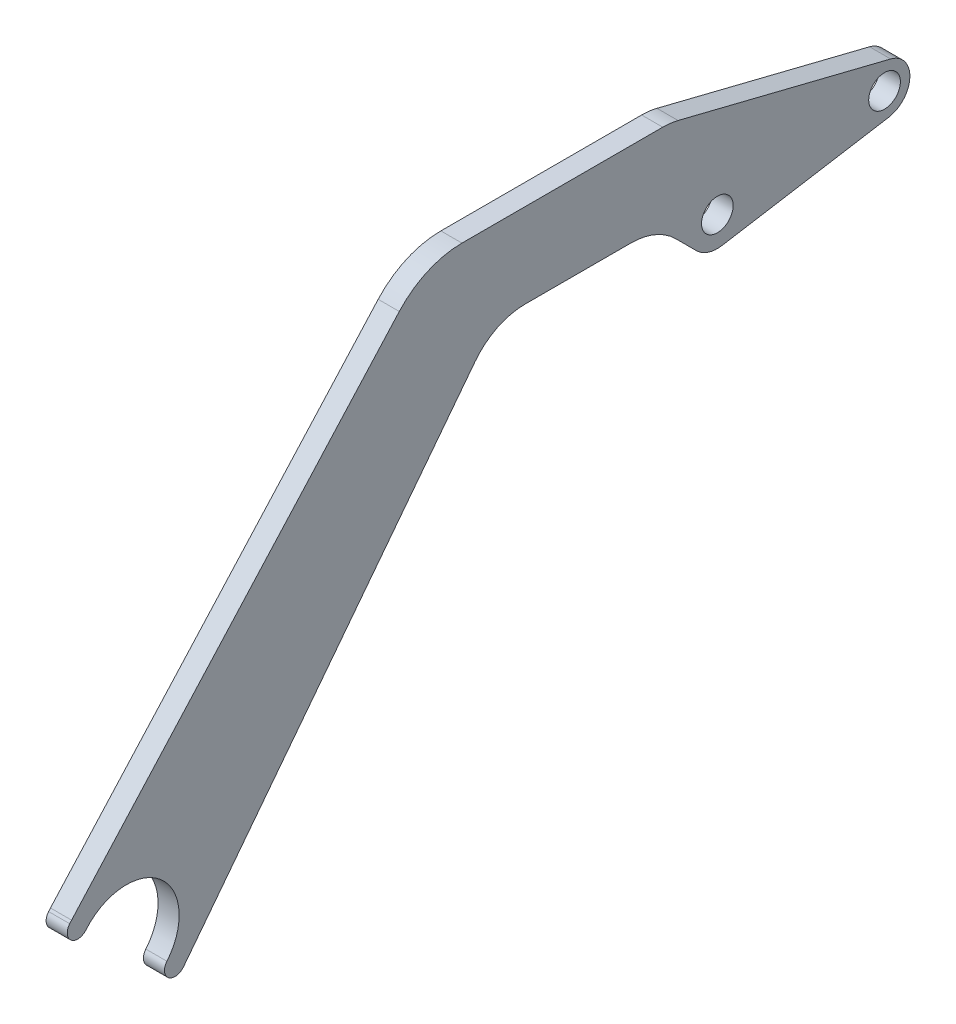
SolidWorks part; units mm, degrees
ref_plane "Front Plane" through (0, 0, 0) normal (0, 0, 1) x (1, 0, 0)
ref_plane "Top Plane" through (0, 0, 0) normal (0, 1, 0) x (1, 0, 0)
ref_plane "Right Plane" through (0, 0, 0) normal (1, 0, 0) x (0, 0, -1)
sketch "Sketch1" plane through (0, 0, 0) normal (1, 0, 0) x (0, 0, -1)
  line L0 (0, 0) -> (98.0709, 0) construction
  line L1 (0, 0) -> (50.3056, 7.07) construction
  line L3 (1.4569, -8.7698) -> (51.5544, -0.447)
  line L4 (-12.5724, 0) -> (-6.2862, -6.2862)
  line L5 (-26.0427, 5.5796) -> (-57.7927, 5.5796)
  line L7 (-1234.6478, -101.6) -> (48765.3522, -101.6) construction
  line L8 (-177.8, -1014.4663) -> (-177.8, 48985.5337) construction
  line L9 (52.1491, 14.4636) -> (-11.8233, 30.4137)
  line L11 (-76.8427, 30.9796) -> (-16.4319, 30.9796)
  line L13 (-194.867, -87.3638) -> (-189.9907, -91.4313) construction
  line L14 (-194.3029, -86.7136) -> (-160.1946, -115.1646) construction
  line L15 (-165.6093, -111.7687) -> (-160.733, -115.8362) construction
  line L16 (-72.8831, -1.8436) -> (-160.1946, -115.1646)
  line L17 (-95.7032, 22.5927) -> (-194.3029, -86.7136)
  circle A0 centre (0, 0) radius 4.7625
  circle A1 centre (50.3056, 7.07) radius 4.7625
  arc A3 (51.5544, -0.447) -> (52.1491, 14.4636) centre (50.3056, 7.07) ccw
  arc A4 (-6.2862, -6.2862) -> (1.4569, -8.7698) centre (0, 0) ccw
  arc A7 (-11.8233, 30.4137) -> (-16.4319, 30.9796) centre (-16.4319, 11.9296) ccw
  arc A8 (-12.5724, 0) -> (-26.0427, 5.5796) centre (-26.0427, -13.4704) ccw
  arc A9 (-57.7927, 5.5796) -> (-72.8831, -1.8436) centre (-57.7927, -13.4704) ccw
  arc A10 (-165.6093, -111.7687) -> (-189.9907, -91.4313) centre (-177.8, -101.6) ccw
  arc A11 (-160.733, -115.8362) -> (-160.1946, -115.1646) centre (-177.8, -101.6) ccw
  arc A12 (-194.3029, -86.7136) -> (-194.867, -87.3638) centre (-177.8, -101.6) ccw
  arc A13 (-95.7032, 22.5927) -> (-76.8427, 30.9796) centre (-76.8427, 5.5796) cw
  arc A14 (-194.867, -87.3638) -> (-189.9907, -91.4313) centre (-192.4288, -89.3975) ccw
  arc A15 (-165.6093, -111.7687) -> (-160.733, -115.8362) centre (-163.1712, -113.8025) ccw
  dimension "D3" = 9.525
  dimension "D4" = 9.525
  dimension "D5" = 8.89
  dimension "D6" = 15.24
  dimension "D7" = 44.45
  dimension "D14" = 25.4
  dimension "D12" = 31.75
  dimension "D13" = 25.4
  dimension "D17" = 19.05
  dimension "D18" = 19.05
  dimension "D1" = 8
  dimension "D2" = 50.8
  dimension "D8" = 101.6
  dimension "D9" = 177.8
  dimension "D10" = 45
  dimension "D11" = 14
  dimension "D16" = 31.75
extrude "Boss-Extrude1" add sketch "Sketch1" along normal blind 6.35
